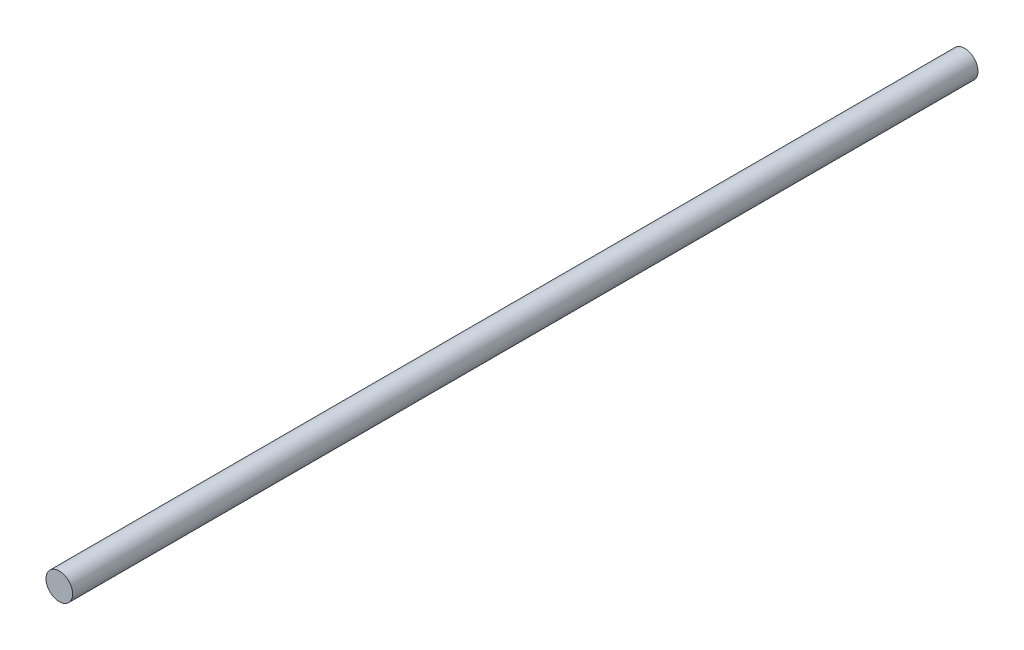
SolidWorks part; units mm, degrees
ref_plane "Plan de face" through (0, 0, 0) normal (0, 0, 1) x (1, 0, 0)
ref_plane "Plan de dessus" through (0, 0, 0) normal (0, 1, 0) x (1, 0, 0)
ref_plane "Plan de droite" through (0, 0, 0) normal (1, 0, 0) x (0, 0, -1)
sketch "Esquisse1" plane through (0, 0, 0) normal (0, 0, 1) x (1, 0, 0)
  circle A0 centre (0, 0) radius 5
  dimension "D1" = 10
extrude "Boss.-Extru.1" add sketch "Esquisse1" along normal blind 340
